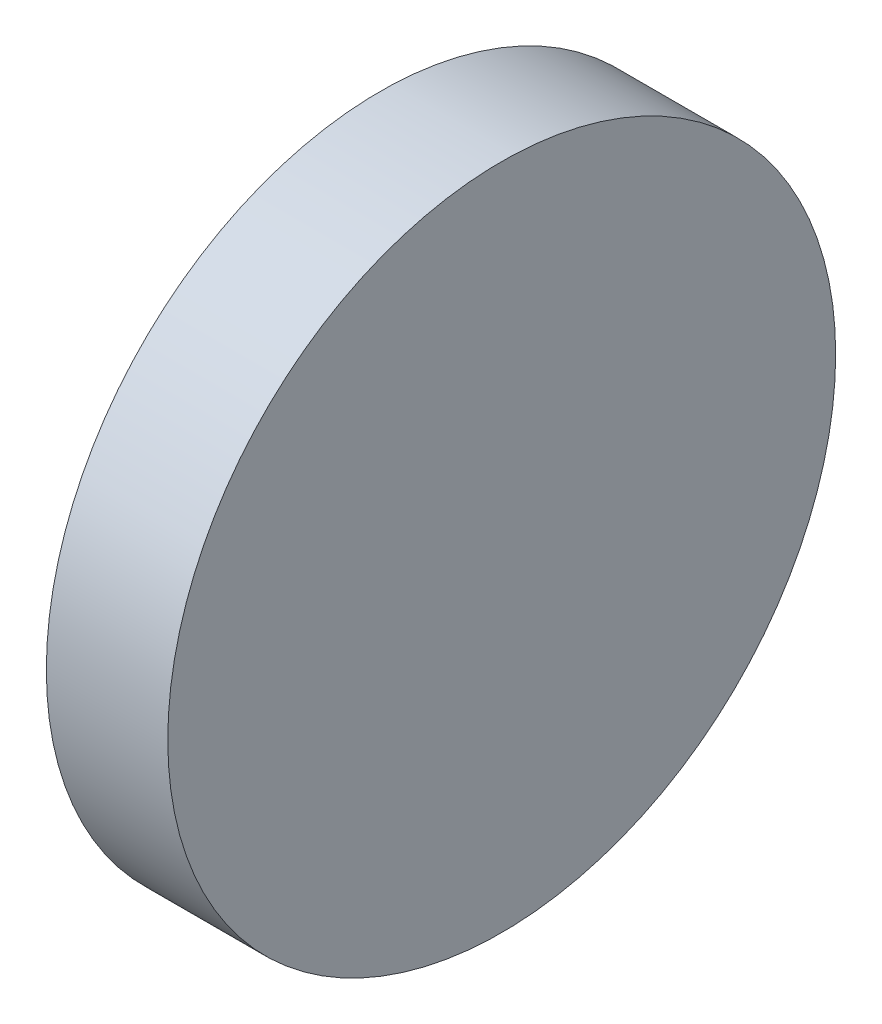
SolidWorks part; units mm, degrees
ref_plane "Front Plane" through (0, 0, 0) normal (0, 0, 1) x (1, 0, 0)
ref_plane "Top Plane" through (0, 0, 0) normal (0, 1, 0) x (1, 0, 0)
ref_plane "Right Plane" through (0, 0, 0) normal (1, 0, 0) x (0, 0, -1)
sketch "Axial profile (mm)" plane through (0, 0, 0) normal (0, 0, 1) x (1, 0, 0)
  line L0 (-110, 0) -> (75, 0) construction
  line L1 (159.7, 0) -> (163.7, 0)
  line L2 (163.7, 0) -> (163.7, 11)
  line L3 (163.7, 11) -> (159.7, 11)
  line L4 (159.7, 11) -> (159.7, 0)
revolve "Full revolution" add sketch "Axial profile (mm)" angle 360 about L0
